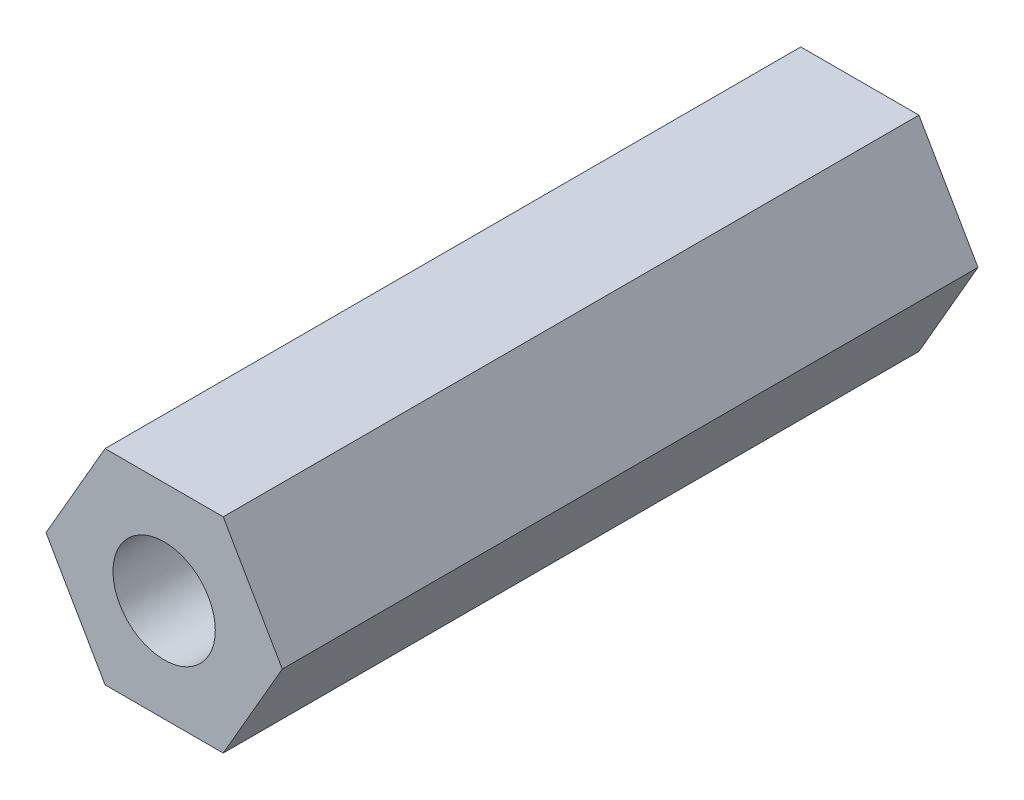
SolidWorks part; units mm, degrees
ref_plane "Front Plane" through (0, 0, 0) normal (0, 0, 1) x (1, 0, 0)
ref_plane "Top Plane" through (0, 0, 0) normal (0, 1, 0) x (1, 0, 0)
ref_plane "Right Plane" through (0, 0, 0) normal (1, 0, 0) x (0, 0, -1)
sketch "Sketch1" plane through (0, 0, 0) normal (0, 0, 1) x (1, 0, 0)
  line L1 (7.3323, 0) -> (3.6662, 6.35)
  line L2 (3.6662, 6.35) -> (-3.6662, 6.35)
  line L3 (-3.6662, 6.35) -> (-7.3323, 0)
  line L4 (-7.3323, 0) -> (-3.6662, -6.35)
  line L5 (-3.6662, -6.35) -> (3.6662, -6.35)
  line L6 (3.6662, -6.35) -> (7.3323, 0)
  circle A0 centre (0, 0) radius 6.35 construction
  circle A1 centre (0, 0) radius 3.175
  dimension "D1" = 12.7
  dimension "D2" = 6.35
extrude "Boss-Extrude1" add sketch "Sketch1" along normal blind 43.18
